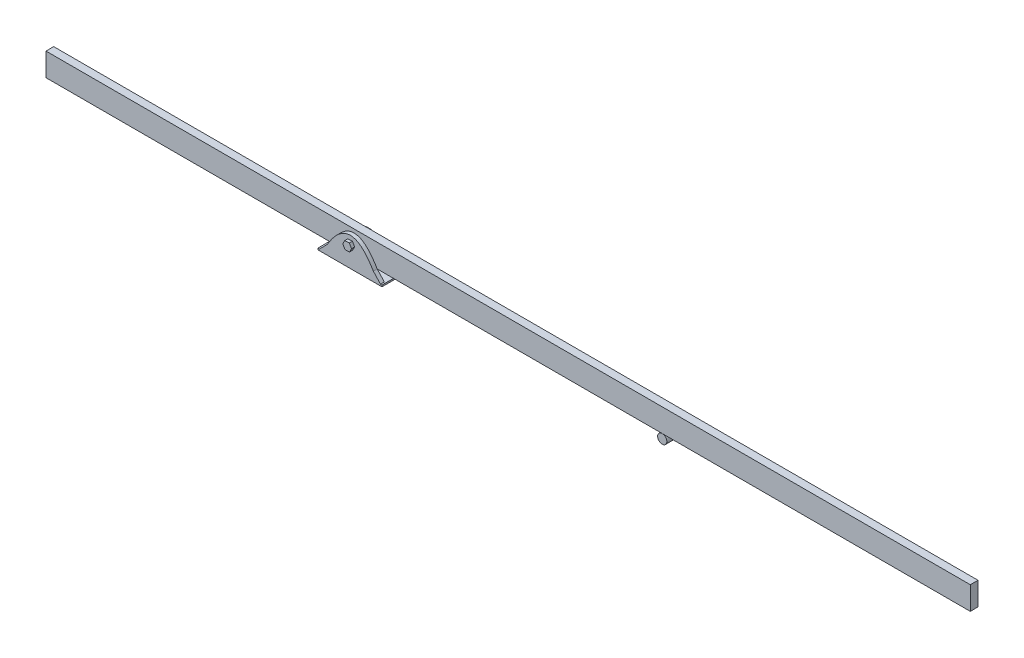
SolidWorks part; units mm, degrees
ref_plane "Front Plane" through (0, 0, 0) normal (0, 0, 1) x (1, 0, 0)
ref_plane "Top Plane" through (0, 0, 0) normal (0, 1, 0) x (1, 0, 0)
ref_plane "Right Plane" through (0, 0, 0) normal (1, 0, 0) x (0, 0, -1)
sketch "Sketch1" plane through (0, 0, 0) normal (0, 0, 1) x (1, 0, 0)
  line L0 (-3000, -75) -> (-1000, -75)
  line L1 (-3000, -75) -> (3000, -75)
  line L2 (-3000, -75) -> (-3000, 75)
  line L3 (-3000, 75) -> (3000, 75)
  line L4 (3000, -75) -> (3000, 75)
  line L5 (-3000, -75) -> (3000, 75) construction
  line L6 (-3000, 75) -> (3000, -75) construction
  line L7 (3000, -75) -> (1000, -75)
  circle A1 centre (1000, -105) radius 30
  circle A3 centre (-1000.0002, -0.0078) radius 25
  point P0 (0, 0)
  dimension "D3" = 2000
  dimension "D4" = 150
  dimension "D1" = 6000
  dimension "D2" = 2000
extrude "Boss-Extrude1" add sketch "Sketch1" along normal blind 50 contours L1 L4 L3 L2 L0 A3 | A1
sketch "Sketch2" plane through (0, 0, 50) normal (0, 0, 1) x (1, 0, 0)
  line L0 (-1000.0002, -25.0078) -> (-1000.0002, -75)
  line L1 (-3000, -75) -> (3000, -75) construction
  line L2 (-1000.0002, -75) -> (-1150.0002, -75)
  line L3 (-1000.0002, -75) -> (-850.0002, -75)
  line L4 (-1150.0002, -75) -> (-1150.0002, -135)
  line L5 (-1150.0002, -75) -> (-1210.0002, -135)
  line L6 (-850.0002, -75) -> (-794.1092, -135)
  line L7 (-794.1092, -135) -> (-1210.0002, -135)
  circle A0 centre (-1000.0002, -0.0078) radius 25 construction
  circle A1 centre (-1000.0002, -0.0078) radius 25
  spline S0 degree 2 poles (-1150.0002, -75) (-1000.0002, 179.2219) (-850.0002, -75) knots 0 0 0 1 1 1
  dimension "D1" = 150
  dimension "D2" = 150
  dimension "D3" = 60
  dimension "D4" = 415.891
extrude "Boss-Extrude2" add sketch "Sketch2" along normal blind 25
sketch "Sketch3" plane through (0, 0, 50) normal (0, 0, -1) x (-1, 0, 0)
  line L0 (794.1092, -135) -> (1210.0002, -135)
  line L1 (1210.0002, -135) -> (1210.0002, -125)
  line L2 (1210.0002, -125) -> (794.1092, -125)
  line L3 (794.1092, -125) -> (794.1092, -135)
  dimension "D1" = 10
extrude "Boss-Extrude3" add sketch "Sketch3" along normal blind 75 and the other way blind 25
sketch "Sketch6" plane through (0, 0, -25) normal (0, 0, -1) x (-1, 0, 0)
  line L0 (803.4244, -125) -> (1200.0002, -125)
  line L1 (1200.0002, -125) -> (1150.0002, -75)
  line L3 (1000.0002, -0.0078) -> (1000.0002, 51.367)
  line L4 (803.4244, -125) -> (850.0002, -75)
  line L5 (3000, -75) -> (-3000, -75) construction
  line L6 (850.0002, -75) -> (803.4244, -125) construction
  circle A0 centre (1000.0002, -0.0078) radius 25
  spline S0 degree 2 poles (850.0002, -75) (1000.0002, 177.734) (1150.0002, -75) knots 0 0 0 1 1 1
extrude "Boss-Extrude4" add sketch "Sketch6" against normal blind 25
ref_plane "Plane1" through (-1210.0002, -125, -25) normal (1, 0, 0) x (0, 0, -1)
sketch "Sketch8" plane through (0, 0, 75) normal (0, 0, 1) x (1, 0, 0)
  line L1 (-986.5698, 25.5954) -> (-1015.4581, 24.4248)
  line L2 (-1015.4581, 24.4248) -> (-1028.8884, -1.1784)
  line L3 (-1028.8884, -1.1784) -> (-1013.4305, -25.611)
  line L4 (-1013.4305, -25.611) -> (-984.5423, -24.4404)
  line L5 (-984.5423, -24.4404) -> (-971.112, 1.1628)
  line L6 (-971.112, 1.1628) -> (-986.5698, 25.5954)
  circle A0 centre (-1000.0002, -0.0078) radius 25.0385 construction
extrude "Boss-Extrude5" add sketch "Sketch8" along normal blind 20
sketch "Sketch10" plane through (0, 0, 75) normal (0, 0, -1) x (-1, 0, 0)
  circle A0 centre (1000.0002, -0.0078) radius 25
extrude "Boss-Extrude6" add sketch "Sketch10" along normal blind 120
sketch "Sketch11" plane through (0, 0, -25) normal (0, 0, -1) x (-1, 0, 0)
  line L1 (1018.8819, 32.6963) -> (981.1185, 32.6963)
  line L2 (981.1185, 32.6963) -> (962.2367, -0.0078)
  line L3 (962.2367, -0.0078) -> (981.1185, -32.7119)
  line L4 (981.1185, -32.7119) -> (1018.8819, -32.7119)
  line L5 (1018.8819, -32.7119) -> (1037.7637, -0.0078)
  line L6 (1037.7637, -0.0078) -> (1018.8819, 32.6963)
  circle A0 centre (1000.0002, -0.0078) radius 32.7041 construction
  circle A1 centre (1000.0002, -0.0078) radius 25
extrude "Boss-Extrude8" add sketch "Sketch11" along normal blind 20 separate body
